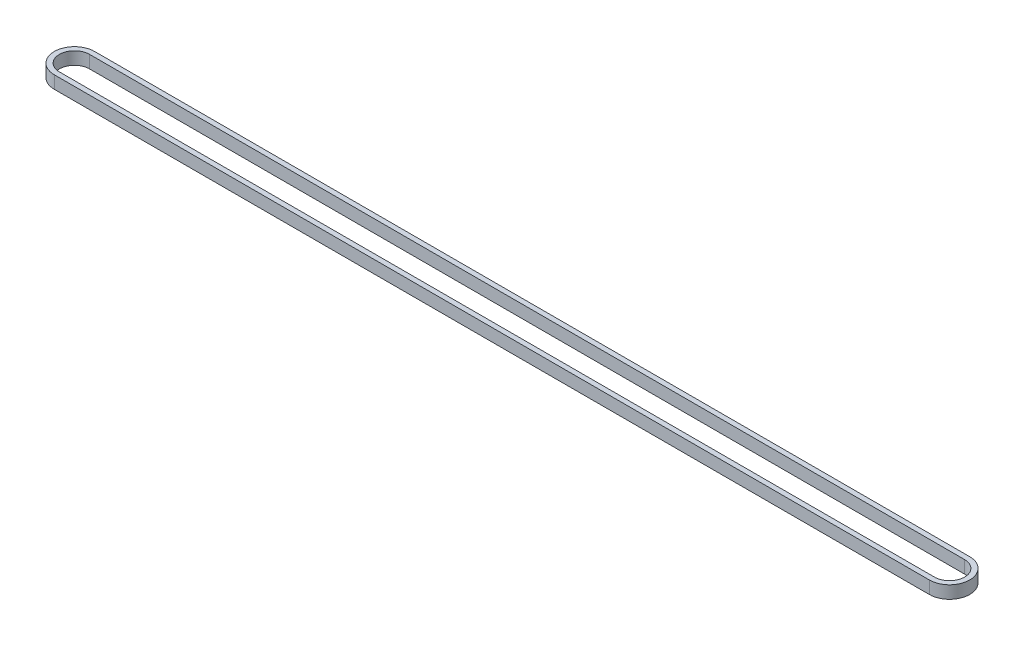
SolidWorks part; units mm, degrees
ref_plane "Front Plane" through (0, 0, 0) normal (0, 0, 1) x (1, 0, 0)
ref_plane "Top Plane" through (0, 0, 0) normal (0, 1, 0) x (1, 0, 0)
ref_plane "Right Plane" through (0, 0, 0) normal (1, 0, 0) x (0, 0, -1)
sketch "Sketch2" plane through (0, 0, 0) normal (0, 1, 0) x (1, 0, 0)
  line L8 (39.2679, 73.0225) -> (386.2679, 73.0225)
  line L9 (39.2679, 71.0225) -> (386.2679, 71.0225)
  line L11 (39.2679, 59.0225) -> (386.2679, 59.0225)
  line L13 (39.2679, 57.0225) -> (386.2679, 57.0225)
  arc A8 (39.2679, 71.0225) -> (39.2679, 59.0225) centre (39.2679, 65.0225) ccw
  arc A9 (386.2679, 59.0225) -> (386.2679, 71.0225) centre (386.2679, 65.0225) ccw
  arc A10 (386.2679, 57.0225) -> (386.2679, 73.0225) centre (386.2679, 65.0225) ccw
  arc A11 (39.2679, 73.0225) -> (39.2679, 57.0225) centre (39.2679, 65.0225) ccw
  dimension "D3" = 2
  dimension "D1" = 12
  dimension "D2" = 347
extrude "Boss-Extrude1" add sketch "Sketch2" along normal blind 5
